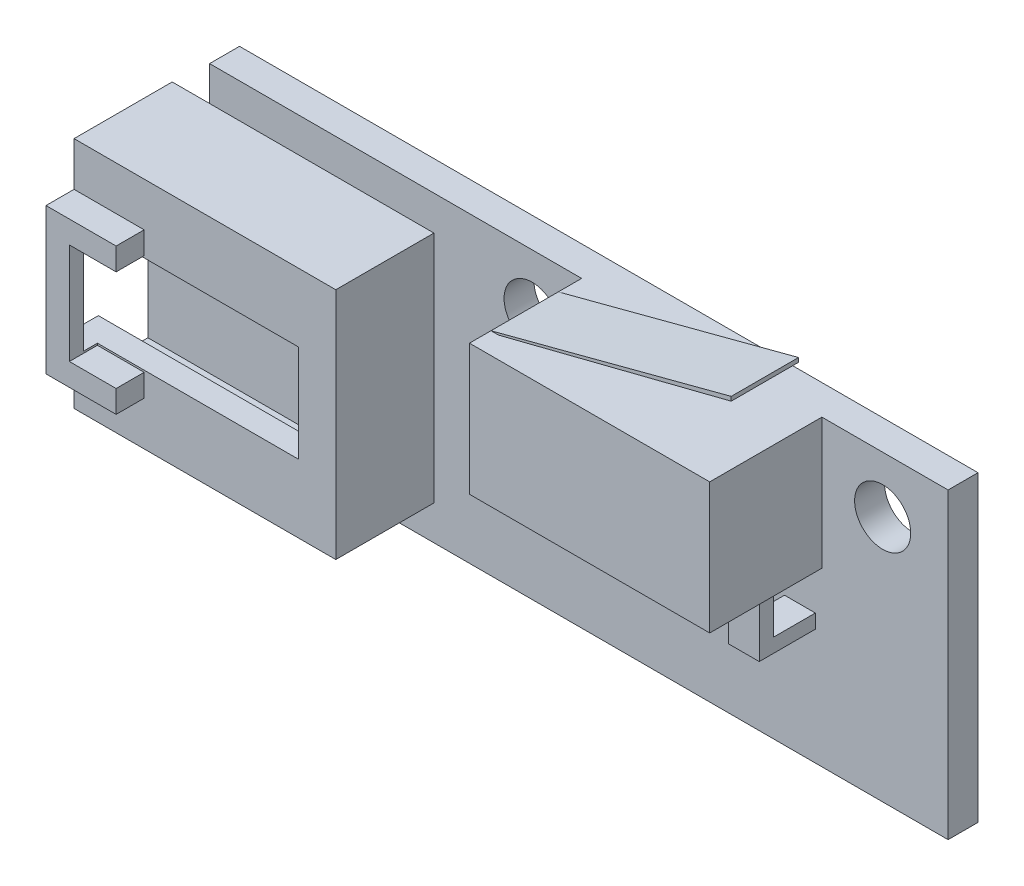
SolidWorks part; units mm, degrees
ref_plane "Front Plane" through (0, 0, 0) normal (0, 0, 1) x (1, 0, 0)
ref_plane "Top Plane" through (0, 0, 0) normal (0, 1, 0) x (1, 0, 0)
ref_plane "Right Plane" through (0, 0, 0) normal (1, 0, 0) x (0, 0, -1)
sketch "Sketch1" plane through (0, 0, 0) normal (0, 0, 1) x (1, 0, 0)
  line L1 (-63.2593, 36.6482) -> (-23.7593, 36.6482)
  line L2 (-63.2593, 36.6482) -> (-63.2593, 20.4482)
  line L3 (-63.2593, 20.4482) -> (-23.7593, 20.4482)
  line L4 (-23.7593, 36.6482) -> (-23.7593, 20.4482)
  circle A0 centre (-27.2593, 33.6482) radius 1.5
  circle A1 centre (-46.0093, 33.6482) radius 1.5
  dimension "D5" = 3
  dimension "D1" = 39.5
  dimension "D2" = 16.2
  dimension "D6" = 18.75
extrude "Boss-Extrude1" add sketch "Sketch1" along normal blind 1.6
sketch "Sketch2" plane through (0, 0, 1.6) normal (0, 0, 1) x (1, 0, 0)
  line L0 (-23.7593, 30.3789) -> (-30.5093, 30.3789)
  line L1 (-23.7593, 20.4482) -> (-23.7593, 36.6482) construction
  line L2 (-23.7593, 36.6482) -> (-63.2593, 36.6482) construction
  line L3 (-30.5093, 36.6482) -> (-43.3593, 36.6482)
  line L4 (-30.5093, 36.6482) -> (-30.5093, 26.6482)
  line L5 (-30.5093, 26.6482) -> (-43.3593, 26.6482)
  line L6 (-43.3593, 36.6482) -> (-43.3593, 26.6482)
  line M5 (-23.7593, 36.6482) -> (-63.2593, 36.6482)
  dimension "D1" = 6.75
  dimension "D2" = 12.85
  dimension "D3" = 10
extrude "Boss-Extrude2" add sketch "Sketch2" along normal blind 6 contours L6 L5 L4 M5
sketch "Sketch3" plane through (0, 0, 7.6) normal (0, 0, 1) x (1, 0, 0)
  line L0 (-30.5093, 26.6482) -> (-43.3593, 26.6482) construction
  line L1 (-43.3593, 26.6482) -> (-30.5093, 26.6482)
  line L2 (-43.3593, 26.6482) -> (-43.3593, 29.6482)
  line L3 (-43.3593, 29.6482) -> (-30.5093, 29.6482)
  line L4 (-30.5093, 26.6482) -> (-30.5093, 29.6482)
  line L5 (-43.3593, 36.6482) -> (-43.3593, 26.6482) construction
  line L6 (-30.5093, 36.6482) -> (-30.5093, 26.6482) construction
  dimension "D1" = 3
extrude "Cut-Extrude1" cut sketch "Sketch3" against normal blind 3
sketch "Sketch4" plane through (0, 0, 4.6) normal (0, 0, 1) x (1, 0, 0)
  line L0 (-30.5093, 27.8565) -> (-32.5093, 27.8565)
  line L1 (-30.5093, 26.6482) -> (-30.5093, 29.6482) construction
  line L2 (-43.3593, 28.1482) -> (-41.3593, 28.1482)
  line L3 (-43.3593, 29.6482) -> (-43.3593, 26.6482) construction
  line L4 (-30.5093, 29.6482) -> (-43.3593, 29.6482) construction
  line L5 (-41.3593, 29.6482) -> (-37.9343, 29.6482)
  line L6 (-41.3593, 29.6482) -> (-41.3593, 26.6482)
  line L7 (-41.3593, 26.6482) -> (-37.9343, 26.6482)
  line L8 (-37.9343, 29.6482) -> (-37.9343, 26.6482)
  line L9 (-43.3593, 26.6482) -> (-30.5093, 26.6482) construction
  line L11 (-32.5093, 29.6482) -> (-35.9343, 29.6482)
  line L12 (-32.5093, 29.6482) -> (-32.5093, 26.6482)
  line L13 (-32.5093, 26.6482) -> (-35.9343, 26.6482)
  line L14 (-35.9343, 29.6482) -> (-35.9343, 26.6482)
  line M2 (-43.3593, 26.6482) -> (-30.5093, 26.6482)
  line M4 (-30.5093, 29.6482) -> (-43.3593, 29.6482)
  dimension "D1" = 2
  dimension "D2" = 2
  dimension "D3" = 3.425
  dimension "D4" = 3.425
extrude "Cut-Extrude3" cut sketch "Sketch4" against normal blind 3 contours L14 L12 M4 M2 | L8 L6 M4 M2
sketch "Sketch5" plane through (-30.5093, 0, 0) normal (1, 0, 0) x (0, 0, -1)
  line L0 (-4.6, 29.6482) -> (-1.6, 29.6482)
  line L5 (-1.6, 36.6482) -> (-1.6, 26.6482) construction
  line L7 (-3.85, 27.3982) -> (-1.6, 27.3982)
  line L8 (-3.85, 27.3982) -> (-3.85, 29.6482)
  line L9 (-3.85, 29.6482) -> (-1.6, 29.6482)
  line L10 (-1.6, 27.3982) -> (-1.6, 29.6482)
  line M4 (-1.6, 26.6482) -> (-1.6, 36.6482)
extrude "Cut-Extrude4" cut sketch "Sketch5" against normal through all contours L8 L7 L0 M4
sketch "Sketch6" plane through (0, 0, 1.6) normal (0, 0, 1) x (1, 0, 0)
  line L0 (-63.2593, 28.5482) -> (-63.2593, 34.7982)
  line L1 (-63.2593, 36.6482) -> (-63.2593, 20.4482) construction
  line L3 (-63.2593, 34.7982) -> (-51.2593, 34.7982)
  line L4 (-63.2593, 34.7982) -> (-63.2593, 22.2982)
  line L5 (-63.2593, 22.2982) -> (-51.2593, 22.2982)
  line L6 (-51.2593, 34.7982) -> (-51.2593, 22.2982)
  line L7 (-63.2593, 34.7982) -> (-65.2593, 34.7982)
  line L8 (-63.2593, 34.7982) -> (-63.2593, 22.2982)
  line L9 (-63.2593, 22.2982) -> (-65.2593, 22.2982)
  line L10 (-65.2593, 34.7982) -> (-65.2593, 22.2982)
  line M13 (-63.2593, 36.6482) -> (-63.2593, 20.4482)
  dimension "D1" = 6.25
  dimension "D2" = 12
  dimension "D3" = 12.5
  dimension "D4" = 2
extrude "Boss-Extrude3" add sketch "Sketch6" along normal blind 6.75 contours L7 L10 L9 M13 | L6 L3 L5 M13
sketch "Sketch7" plane through (0, 0, 8.35) normal (0, 0, 1) x (1, 0, 0)
  line L0 (-65.2593, 32.4482) -> (-65.2593, 24.6482)
  line L1 (-65.2593, 34.7982) -> (-65.2593, 22.2982) construction
  line L2 (-65.2593, 24.6482) -> (-61.5093, 24.6482)
  line L3 (-61.5093, 24.6482) -> (-61.5093, 25.8482)
  line L4 (-61.5093, 25.8482) -> (-64.0093, 25.8482)
  line L5 (-64.0093, 25.8482) -> (-64.0093, 31.2482)
  line L6 (-65.2593, 32.4482) -> (-65.2593, 34.7982)
  line L7 (-61.5093, 31.2482) -> (-64.0093, 31.2482)
  line L8 (-61.5093, 32.4482) -> (-61.5093, 31.2482)
  line L9 (-65.2593, 32.4482) -> (-61.5093, 32.4482)
  line L10 (-65.2593, 34.7982) -> (-51.2593, 34.7982)
  line L11 (-51.2593, 34.7982) -> (-51.2593, 22.2982)
  line L12 (-51.2593, 22.2982) -> (-65.2593, 22.2982)
  line L13 (-51.2593, 22.2982) -> (-65.2593, 22.2982) construction
  line L14 (-65.2593, 22.2982) -> (-65.2593, 24.6482)
  point P13 (-65.2593, 28.5482)
  line M1 (-51.2593, 34.7982) -> (-65.2593, 34.7982)
  line M2 (-65.2593, 34.7982) -> (-65.2593, 22.2982)
  line M3 (-65.2593, 22.2982) -> (-51.2593, 22.2982)
  line M4 (-51.2593, 22.2982) -> (-51.2593, 34.7982)
  dimension "D1" = 3.9
  dimension "D2" = 3.75
  dimension "D3" = 1.2
  dimension "D4" = 2.5
extrude "Cut-Extrude5" cut sketch "Sketch7" against normal blind 1.5 contours L9 L8 L7 L5 L4 L3 L2 M2 M3 M4 M1
sketch "Sketch8" plane through (-65.2593, 0, 0) normal (-1, 0, 0) x (0, 0, 1)
  line L0 (6.85, 32.4482) -> (6.85, 31.1482)
  line L1 (6.85, 34.7982) -> (5.55, 34.7982)
  line L2 (6.85, 34.7982) -> (6.85, 33.4982)
  line L3 (6.85, 33.4982) -> (5.55, 33.4982)
  line L4 (5.55, 34.7982) -> (5.55, 33.4982)
  line L5 (1.6, 22.2982) -> (2.9, 22.2982)
  line L6 (1.6, 22.2982) -> (1.6, 23.5982)
  line L7 (1.6, 23.5982) -> (2.9, 23.5982)
  line L8 (2.9, 22.2982) -> (2.9, 23.5982)
  line L9 (5.55, 33.4982) -> (2.9, 33.4982)
  line L10 (5.55, 33.4982) -> (5.55, 23.5982)
  line L11 (5.55, 23.5982) -> (2.9, 23.5982)
  line L12 (2.9, 33.4982) -> (2.9, 23.5982)
  line L13 (6.85, 24.6482) -> (6.85, 25.9482)
  line L14 (6.85, 31.1482) -> (5.55, 31.1482)
  line L15 (6.85, 25.9482) -> (5.55, 25.9482)
  line L16 (6.85, 31.1482) -> (7.6, 31.1482)
  line L17 (6.85, 25.9482) -> (7.6, 25.9482)
  line L18 (7.6, 31.1482) -> (7.6, 25.9482)
  dimension "D1" = 1.3
  dimension "D2" = 1.3
  dimension "D3" = 1.3
  dimension "D4" = 1.3
  dimension "D5" = 1.3
  dimension "D6" = 1.3
  dimension "D7" = 0.75
  dimension "D8" = 0.75
extrude "Cut-Extrude6" cut sketch "Sketch8" against normal blind 12 contours L18 L16 L14 L10 L15 L17 | L9 L12 L11 L10
sketch "Sketch9" plane through (0, 0, 4.6) normal (0, 0, 1) x (1, 0, 0)
  line L0 (-32.5093, 26.6482) -> (-30.5093, 26.6482) construction
  line L1 (-30.5093, 29.6482) -> (-30.8593, 29.6482)
  line L2 (-30.5093, 29.6482) -> (-30.5093, 26.6482)
  line L3 (-30.5093, 26.6482) -> (-30.8593, 26.6482)
  line L4 (-30.8593, 29.6482) -> (-30.8593, 26.6482)
  line L5 (-43.3593, 26.6482) -> (-41.3593, 26.6482) construction
  line L6 (-43.3593, 29.6482) -> (-43.0093, 29.6482)
  line L7 (-43.3593, 29.6482) -> (-43.3593, 26.6482)
  line L8 (-43.3593, 26.6482) -> (-43.0093, 26.6482)
  line L9 (-43.0093, 29.6482) -> (-43.0093, 26.6482)
  line L10 (-37.9343, 26.6482) -> (-35.9343, 26.6482) construction
  line L11 (-37.9343, 29.6482) -> (-37.7593, 29.6482)
  line L12 (-37.9343, 29.6482) -> (-37.9343, 26.6482)
  line L13 (-37.9343, 26.6482) -> (-37.7593, 26.6482)
  line L14 (-37.7593, 29.6482) -> (-37.7593, 26.6482)
  line L16 (-35.9343, 29.6482) -> (-36.1093, 29.6482)
  line L17 (-35.9343, 29.6482) -> (-35.9343, 26.6482)
  line L18 (-35.9343, 26.6482) -> (-36.1093, 26.6482)
  line L19 (-36.1093, 29.6482) -> (-36.1093, 26.6482)
  dimension "D1" = 0.35
  dimension "D2" = 0.35
  dimension "D3" = 0.175
  dimension "D4" = 0.175
extrude "Cut-Extrude7" cut sketch "Sketch9" against normal up to surface (3 mm away) up to face at (-44.5093, 33.6482, 1.6)
sketch "Sketch10" plane through (0, 0, 7.6) normal (0, 0, 1) x (1, 0, 0)
  line L0 (-43.3593, 36.6482) -> (-30.4937, 40.0378)
  line L1 (-30.5093, 39.8093) -> (-30.5093, 40.0337)
  line L2 (-42.9541, 36.6482) -> (-30.5093, 39.8093)
  line L3 (-30.5093, 36.6482) -> (-43.3593, 36.6482) construction
  line L4 (-43.3593, 36.6482) -> (-42.9541, 36.6482)
  line L5 (-30.4937, 40.0378) -> (-30.5093, 39.8093)
  line L6 (-43.3593, 36.6482) -> (-42.9541, 36.6482)
  line L7 (-42.9541, 36.6482) -> (-42.9493, 36.6476)
  line M3 (-30.5093, 36.6482) -> (-43.3593, 36.6482)
extrude "Boss-Extrude4" add sketch "Sketch10" against normal blind 4.75 contours L2 L1 L0 M3
sketch "Sketch11" plane through (0, 36.6482, 0) normal (0, 1, 0) x (1, 0, 0)
  line L0 (-43.3593, -7.6) -> (-43.3593, -2.85) construction
  line L1 (-30.5093, -7.6) -> (-43.3593, -7.6)
  line L2 (-30.5093, -7.6) -> (-30.5093, -6.45)
  line L3 (-30.5093, -6.45) -> (-43.3593, -6.45)
  line L4 (-43.3593, -7.6) -> (-43.3593, -6.45)
  dimension "D1" = 1.15
extrude "Cut-Extrude8" cut sketch "Sketch11" along normal blind 4.75
